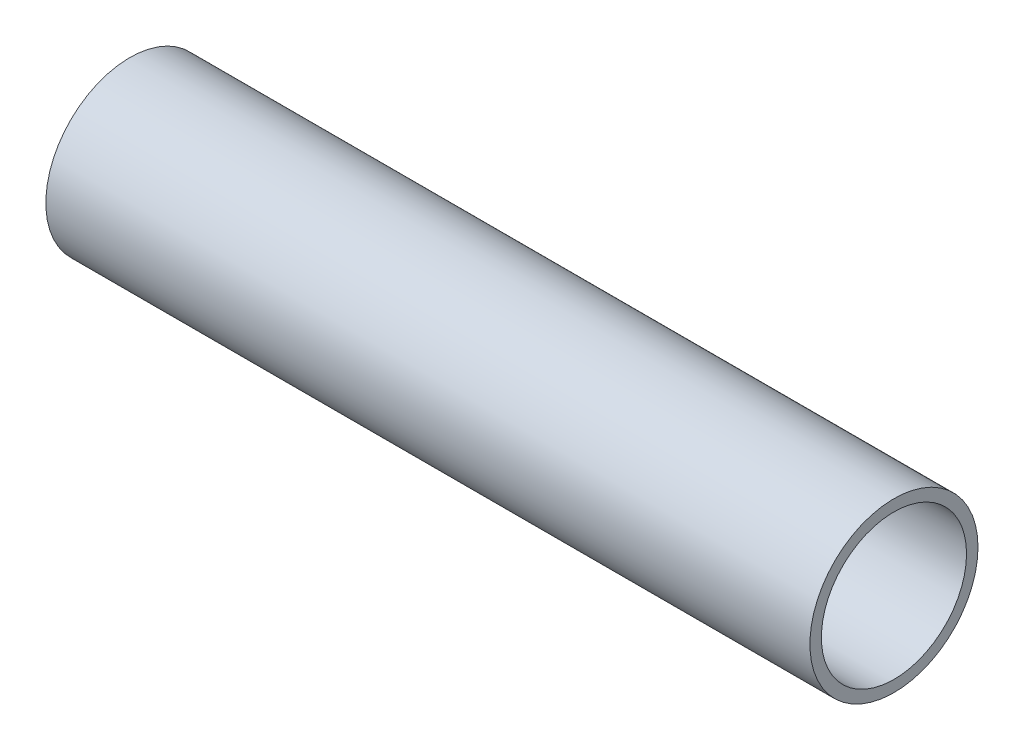
SolidWorks part; units mm, degrees
material "PVC 0.007 Plasticized"
ref_plane "Front Plane" through (0, 0, 0) normal (0, 0, 1) x (1, 0, 0)
ref_plane "Top Plane" through (0, 0, 0) normal (0, 1, 0) x (1, 0, 0)
ref_plane "Right Plane" through (0, 0, 0) normal (1, 0, 0) x (0, 0, -1)
sketch "Sketch1" plane through (0, 0, 0) normal (1, 0, 0) x (0, 0, -1)
  circle A0 centre (0, 0) radius 11
  circle A1 centre (0, 0) radius 9.5
  dimension "D1" = 1.5
extrude "Boss-Extrude1" add sketch "Sketch1" along normal blind 100
